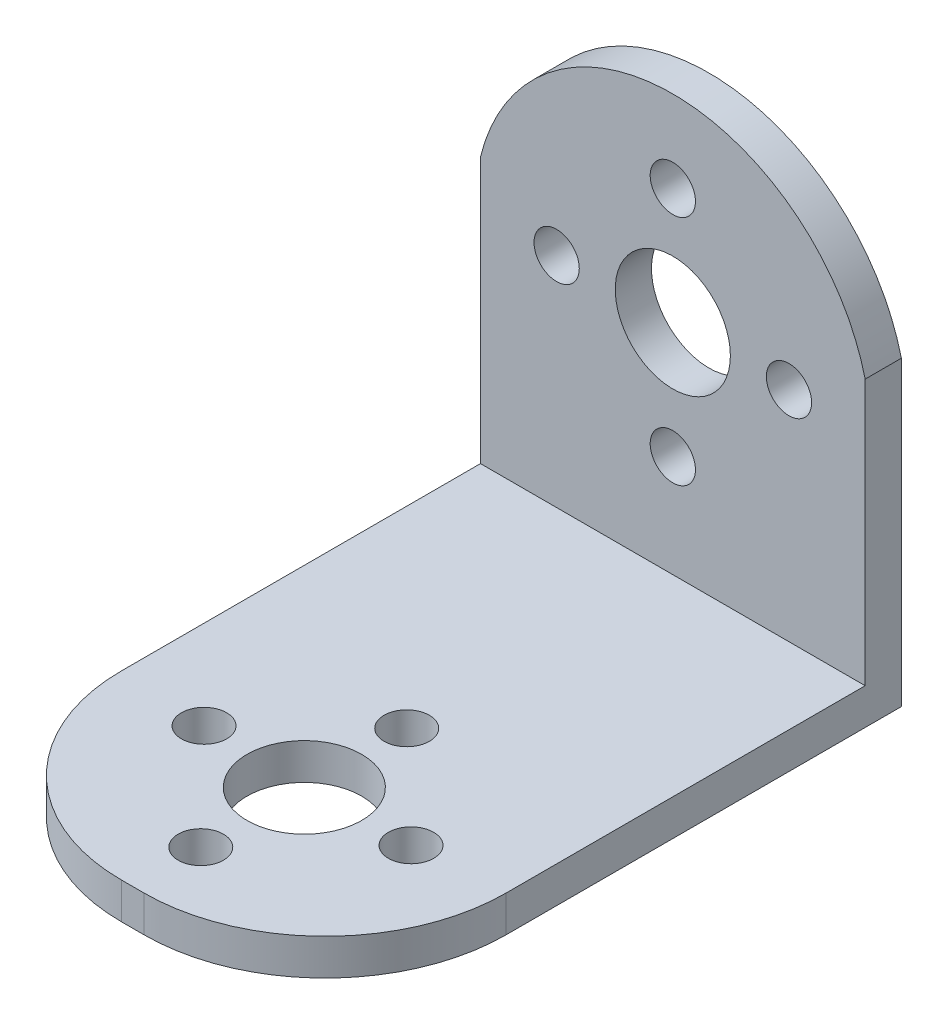
SolidWorks part; units mm, degrees
ref_plane "Front Plane" through (0, 0, 0) normal (0, 0, 1) x (1, 0, 0)
ref_plane "Top Plane" through (0, 0, 0) normal (0, 1, 0) x (1, 0, 0)
ref_plane "Right Plane" through (0, 0, 0) normal (1, 0, 0) x (0, 0, -1)
sketch "Sketch1" plane through (0, 0, 0) normal (0, 0, 1) x (1, 0, 0)
  line L0 (0, 0) -> (25.5, 0)
  line L1 (0, 0) -> (0, 20)
  line L2 (0, -16.5) -> (0, 16.5) construction
  line L3 (0, 30) -> (70.6713, 30) construction
  line L4 (38.8692, 0) -> (-38.8692, 0) construction
  line L5 (25.5, 0) -> (25.5, 20)
  line L6 (12.75, 26.1587) -> (12.75, 7.585) construction
  line L7 (12.75, 30) -> (12.75, 0) construction
  line L8 (0, 20) -> (25.5, 20) construction
  arc A0 (0, 20) -> (25.5, 20) centre (12.75, 16.8719) cw
  circle A1 centre (12.75, 24.5719) radius 1.5
  circle A2 centre (12.75, 16.8719) radius 3.815
  circle A3 centre (20.45, 16.8719) radius 1.5
  circle A4 centre (12.75, 9.1719) radius 1.5
  circle A5 centre (5.05, 16.8719) radius 1.5
  point P4 (0, 0)
  point P24 (14.0945, 14.3706)
  point P27 (0, 0)
  dimension "D1" = 30
  dimension "D2" = 25.5
  dimension "D3" = 20
  dimension "D4" = 20
  dimension "D5" = 7.7
  dimension "D6" = 7.7
  dimension "D7" = 7.7
  dimension "D8" = 7.7
extrude "Boss-Extrude1" add sketch "Sketch1" along normal blind 2.4 contours A0 L5 L0 L1
sketch "Sketch2" plane through (0, 0, 2.4) normal (0, 0, 1) x (1, 0, 0)
  line L0 (25.5, 0) -> (25.5, 20) construction
  line L1 (0, 0) -> (25.5, 0)
  line L2 (0, 0) -> (0, 2.4)
  line L3 (0, 2.4) -> (25.5, 2.4)
  line L4 (25.5, 0) -> (25.5, 2.4)
  point P7 (-20.089, -10.9532)
  dimension "D1" = 2.4
extrude "Boss-Extrude2" add sketch "Sketch2" along normal blind 35.8
sketch "Sketch3" plane through (0, 0, 0) normal (0, -1, 0) x (1, 0, 0)
  line L0 (0, -16.5) -> (0, 16.5) construction
  line L1 (12, 38.2) -> (13.5, 38.2)
  line L5 (0, 38.2) -> (25.5, 38.2) construction
  line L6 (0, 26.2) -> (0, 38.2)
  line L7 (0, 38.2) -> (12, 38.2)
  line L8 (13.5, 38.2) -> (25.5, 38.2)
  line L9 (25.5, 26.2) -> (25.5, 38.2)
  arc A0 (13.5, 38.2) -> (25.5, 26.2) centre (13.5, 26.2) cw
  arc A1 (12, 38.2) -> (0, 26.2) centre (12, 26.2) ccw
  point P11 (25.5, 38.2)
  point P14 (0, 38.2)
  line M10 (25.5, 0) -> (25.5, 38.2)
  line M11 (25.5, 38.2) -> (0, 38.2)
  line M12 (0, 38.2) -> (0, 0)
  dimension "D2" = 12
  dimension "D3" = 12
  dimension "D1" = 25.5
extrude "Cut-Extrude1" cut sketch "Sketch3" against normal blind 35.8 contours A1 M11 M12 | A0 M11 M10
sketch "Sketch4" plane through (0, 0, 0) normal (0, -1, 0) x (1, 0, 0)
  line L1 (19.61, 25.1122) -> (19.61, 28.1122) construction
  line L2 (11.25, 33.6872) -> (14.25, 33.6872) construction
  line L3 (11.25, 20.0372) -> (14.25, 20.0372) construction
  line L4 (12.75, 38.2) -> (12.75, 0) construction
  line L5 (12, 38.2) -> (13.5, 38.2) construction
  line L6 (0, 0) -> (25.5, 0) construction
  circle A0 centre (12.75, 26.8238) radius 3.8
  circle A1 centre (5.89, 26.6122) radius 1.501
  circle A2 centre (19.61, 26.6122) radius 1.5
  circle A3 centre (12.75, 33.6872) radius 1.5
  circle A4 centre (12.75, 20.0372) radius 1.5
  point P24 (0, 0)
  dimension "D1" = 6.8634
  dimension "D2" = 6.86
  dimension "D3" = 6.86
extrude "Cut-Extrude2" cut sketch "Sketch4" against normal blind 35.8
